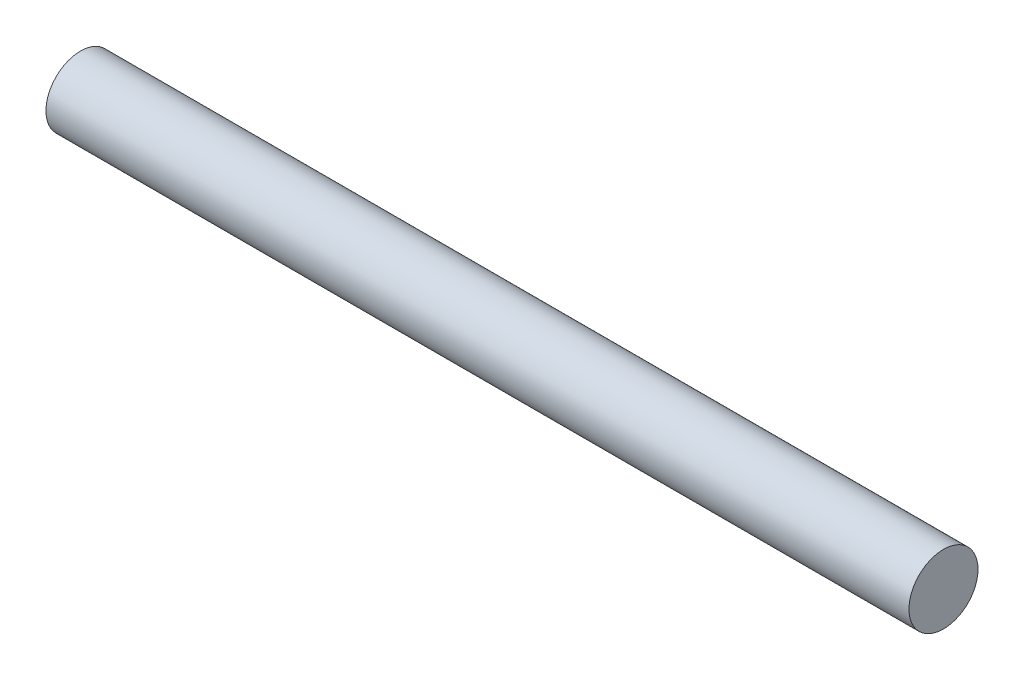
SolidWorks part; units mm, degrees
ref_plane "Front Plane" through (0, 0, 0) normal (0, 0, 1) x (1, 0, 0)
ref_plane "Top Plane" through (0, 0, 0) normal (0, 1, 0) x (1, 0, 0)
ref_plane "Right Plane" through (0, 0, 0) normal (1, 0, 0) x (0, 0, -1)
sketch "Sketch1" plane through (0, 0, 0) normal (1, 0, 0) x (0, 0, -1)
  circle A0 centre (0, 0) radius 4
  dimension "D1" = 8
extrude "Boss-Extrude1" add sketch "Sketch1" along normal blind 100
sketch "Sketch2" plane through (0, 0, 0) normal (0, 0, 1) x (1, 0, 0)
  line L0 (100, 0) -> (120.7431, 0)
  line L1 (100, -4) -> (100, 4) construction
